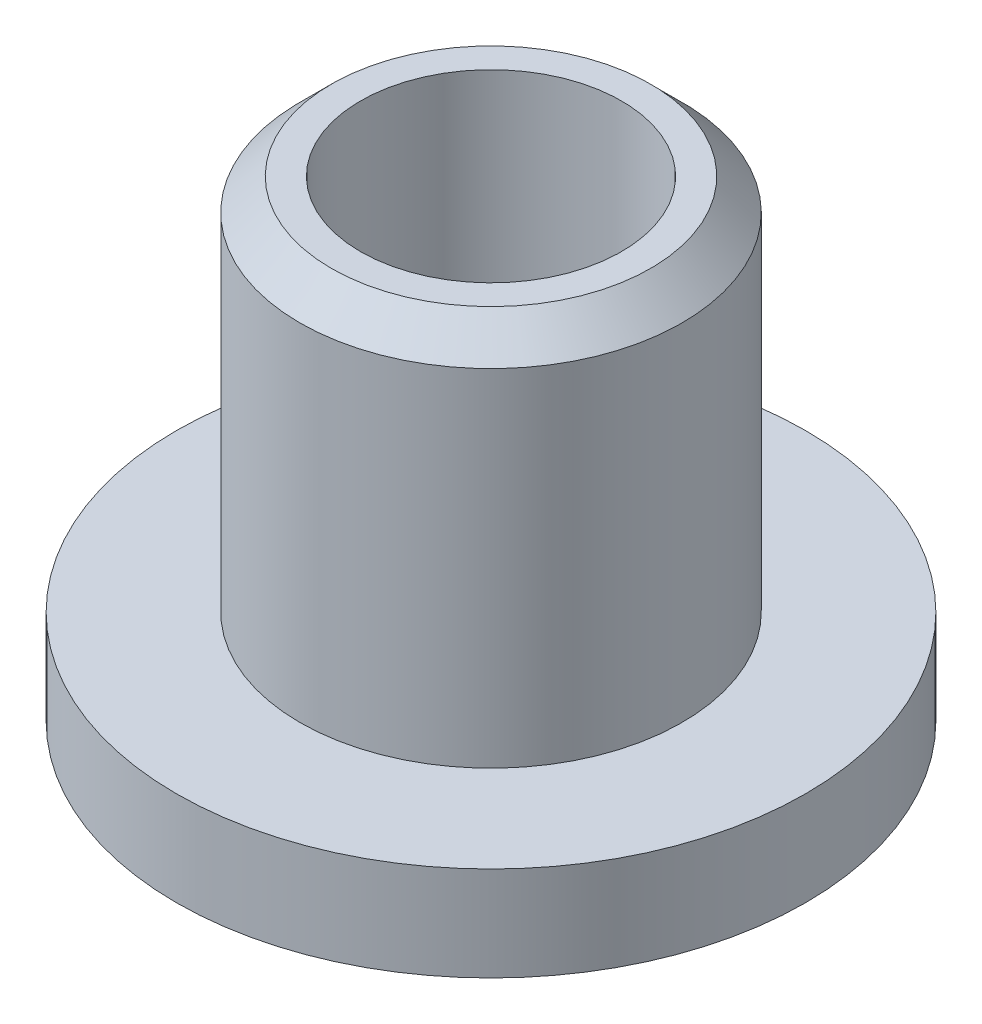
SolidWorks part; units mm, degrees
material "PA Typ 6"
ref_plane "Ebene vorne" through (0, 0, 0) normal (0, 0, 1) x (1, 0, 0)
ref_plane "Ebene oben" through (0, 0, 0) normal (0, 1, 0) x (1, 0, 0)
ref_plane "Ebene rechts" through (0, 0, 0) normal (1, 0, 0) x (0, 0, -1)
sketch "Skizze1" plane through (0, 0, 0) normal (0, 1, 0) x (1, 0, 0)
  circle A0 centre (0, 0) radius 10
  dimension "D1" = 20
extrude "Aufsatz-Linear austragen1" add sketch "Skizze1" along normal blind 3
sketch "Skizze2" plane through (0, 3, 0) normal (0, 1, 0) x (1, 0, 0)
  circle A0 centre (0, 0) radius 6.075
  dimension "D1" = 12.15
extrude "Aufsatz-Linear austragen2" add sketch "Skizze2" along normal blind 12
sketch "Skizze3" plane through (0, 15, 0) normal (0, 1, 0) x (1, 0, 0)
  circle A0 centre (0, 0) radius 4.15
  dimension "D1" = 8.3
extrude "Schnitt-Linear austragen1" cut sketch "Skizze3" against normal through all
chamfer "Fase1" distance 1 angle 45 2 edges at (0, 15, 6.075) (0, 0, 4.15)
